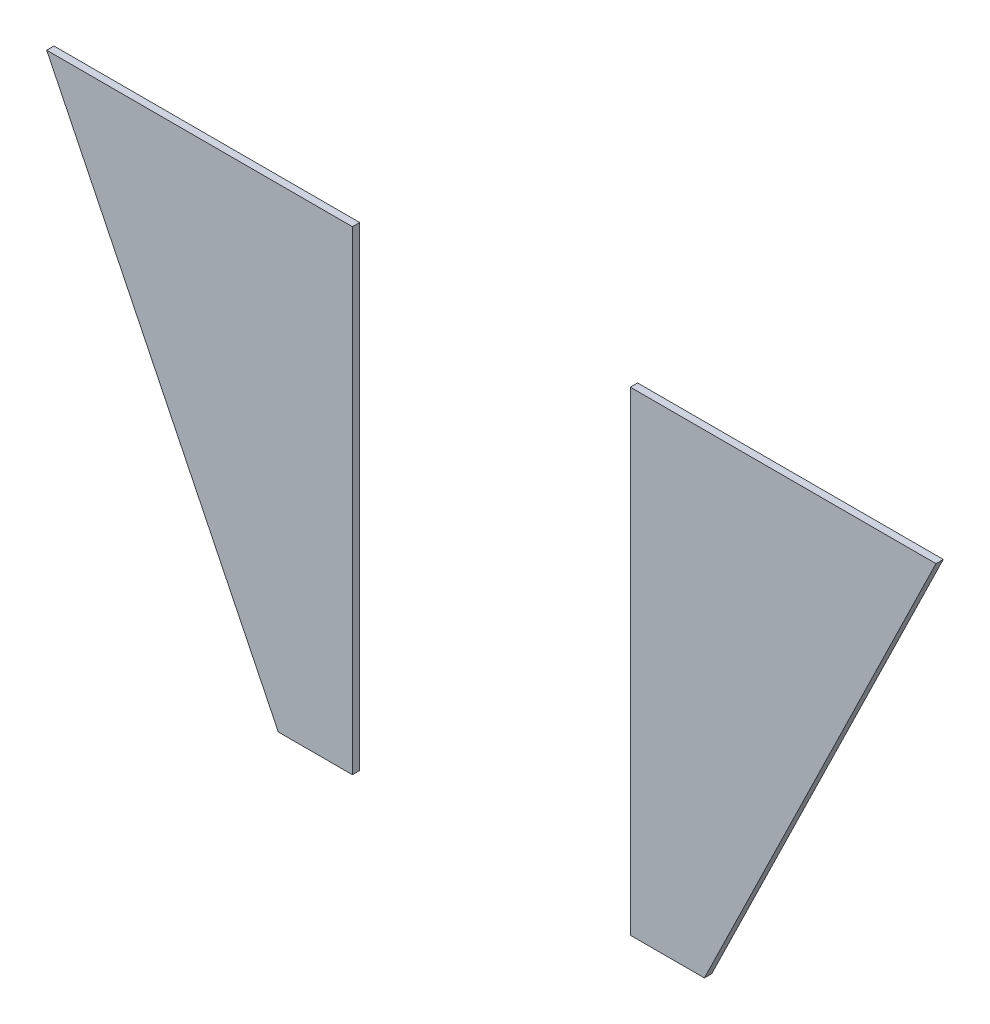
SolidWorks part; units mm, degrees
ref_plane "Front" through (0, 0, 0) normal (0, 0, 1) x (1, 0, 0)
ref_plane "Top" through (0, 0, 0) normal (0, 1, 0) x (1, 0, 0)
ref_plane "Right" through (0, 0, 0) normal (1, 0, 0) x (0, 0, -1)
sketch "草图1" plane through (0, 0, 0) normal (0, 0, 1) x (1, 0, 0)
  line L0 (238.9927, 0) -> (238.9927, -17.4891) construction
  line L1 (92.9427, 2.886) -> (143.7427, 2.886)
  line L2 (92.9427, 2.886) -> (-65.8073, 328.256)
  line L3 (-65.8073, 328.256) -> (143.7427, 328.256)
  line L4 (143.7427, 328.256) -> (143.7427, 2.886)
  line L5 (334.2427, 328.256) -> (334.2427, 2.886)
  line L6 (543.7927, 328.256) -> (334.2427, 328.256)
  line L7 (385.0427, 2.886) -> (543.7927, 328.256)
  line L8 (385.0427, 2.886) -> (334.2427, 2.886)
  point P7 (238.9927, 2.886)
  point P8 (238.9927, 328.256)
  dimension "D1" = 146.05
  dimension "D2" = 95.25
  dimension "D3" = 304.8
  dimension "D4" = 325.37
extrude "凸台-拉伸1" add sketch "草图1" along normal blind 5
